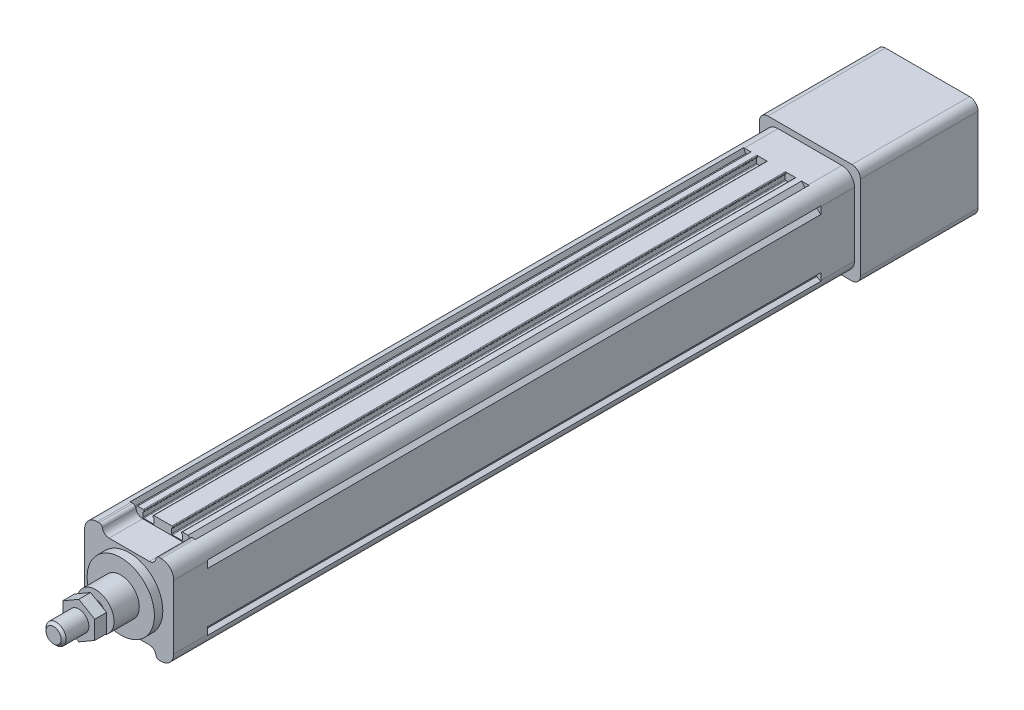
SolidWorks part; units mm, degrees
ref_plane "Front" through (0, 0, 0) normal (0, 0, 1) x (1, 0, 0)
ref_plane "Top" through (0, 0, 0) normal (0, 1, 0) x (1, 0, 0)
ref_plane "Right" through (0, 0, 0) normal (1, 0, 0) x (0, 0, -1)
sketch "草图1" plane through (0, 0, 0) normal (0, 0, 1) x (1, 0, 0)
  line L0 (19.7737, 3) -> (23.3, 3)
  line L1 (23.3, 3) -> (23.3, -3)
  line L2 (23.3, -3) -> (19.7737, -3)
  line L3 (-19.7737, -3) -> (-23.3, -3)
  line L4 (-23.3, -3) -> (-23.3, 3)
  line L5 (-23.3, 3) -> (-19.7737, 3)
  line L6 (-18.2, 24) -> (-19.4434, 26.4869)
  line L7 (-26.4869, 19.4434) -> (-24, 18.2)
  line L8 (-24, 18.2) -> (-24, 17.1)
  line L9 (-24, 17.1) -> (-26.5, 15)
  line L10 (-26.5, 15) -> (-26.5, -15)
  line L11 (-26.5, -15) -> (-24, -17.1)
  line L12 (-24, -17.1) -> (-24, -18.2)
  line L13 (-24, -18.2) -> (-26.4869, -19.4434)
  line L14 (-19.4434, -26.4869) -> (-18.2, -24)
  line L15 (-18.2, -24) -> (-17.1, -24)
  line L16 (-17.1, -24) -> (-15, -26.5)
  line L17 (-15, -26.5) -> (-11.65, -26.5)
  line L18 (-11.25, -26.1) -> (-11.25, -25.6)
  line L19 (-11.65, -25.2) -> (-11.75, -25.2)
  line L20 (-11.75, -25.2) -> (-11.75, -22.4)
  line L21 (-11.35, -22) -> (-5.65, -22)
  line L22 (-5.25, -22.4) -> (-5.25, -25.2)
  line L23 (-5.25, -25.2) -> (-5.35, -25.2)
  line L24 (-5.75, -25.6) -> (-5.75, -26.1)
  line L25 (-5.35, -26.5) -> (5.35, -26.5)
  line L26 (5.75, -26.1) -> (5.75, -25.6)
  line L27 (5.35, -25.2) -> (5.25, -25.2)
  line L28 (5.25, -25.2) -> (5.25, -22.4)
  line L29 (5.65, -22) -> (11.35, -22)
  line L30 (11.75, -22.4) -> (11.75, -25.2)
  line L31 (11.75, -25.2) -> (11.65, -25.2)
  line L32 (11.25, -25.6) -> (11.25, -26.1)
  line L33 (11.65, -26.5) -> (15, -26.5)
  line L34 (15, -26.5) -> (17.1, -24)
  line L35 (17.1, -24) -> (18.2, -24)
  line L36 (18.2, -24) -> (19.4434, -26.4869)
  line L37 (26.4869, -19.4434) -> (24, -18.2)
  line L38 (24, -18.2) -> (24, -17.1)
  line L39 (24, -17.1) -> (26.5, -15)
  line L40 (26.5, -15) -> (26.5, 15)
  line L41 (26.5, 15) -> (24, 17.1)
  line L42 (24, 17.1) -> (24, 18.2)
  line L43 (24, 18.2) -> (26.4869, 19.4434)
  line L44 (19.4434, 26.4869) -> (18.2, 24)
  line L45 (18.2, 24) -> (17.1, 24)
  line L46 (17.1, 24) -> (15, 26.5)
  line L47 (15, 26.5) -> (11.65, 26.5)
  line L48 (11.25, 26.1) -> (11.25, 25.6)
  line L49 (11.65, 25.2) -> (11.75, 25.2)
  line L50 (11.75, 25.2) -> (11.75, 22.4)
  line L51 (11.35, 22) -> (5.65, 22)
  line L52 (5.25, 22.4) -> (5.25, 25.2)
  line L53 (5.25, 25.2) -> (5.35, 25.2)
  line L54 (5.75, 25.6) -> (5.75, 26.1)
  line L55 (5.35, 26.5) -> (-5.35, 26.5)
  line L56 (-5.75, 26.1) -> (-5.75, 25.6)
  line L57 (-5.35, 25.2) -> (-5.25, 25.2)
  line L58 (-5.25, 25.2) -> (-5.25, 22.4)
  line L59 (-5.65, 22) -> (-11.35, 22)
  line L60 (-11.75, 22.4) -> (-11.75, 25.2)
  line L61 (-11.75, 25.2) -> (-11.65, 25.2)
  line L62 (-11.25, 25.6) -> (-11.25, 26.1)
  line L63 (-11.65, 26.5) -> (-15, 26.5)
  line L64 (-15, 26.5) -> (-17.1, 24)
  line L65 (-17.1, 24) -> (-18.2, 24)
  arc A0 (19.7737, 3) -> (-19.7737, 3) centre (0, 0) ccw
  arc A1 (-19.7737, -3) -> (19.7737, -3) centre (0, 0) ccw
  circle A2 centre (19, 19) radius 2.1
  circle A3 centre (19, -19) radius 2.1
  circle A4 centre (-19, -19) radius 2.1
  circle A5 centre (-19, 19) radius 2.1
  arc A6 (-19.4434, 26.4869) -> (-26.4869, 19.4434) centre (-19, 19) ccw
  arc A7 (-26.4869, -19.4434) -> (-19.4434, -26.4869) centre (-19, -19) ccw
  arc A8 (-11.65, -26.5) -> (-11.25, -26.1) centre (-11.65, -26.1) ccw
  arc A9 (-11.25, -25.6) -> (-11.65, -25.2) centre (-11.65, -25.6) ccw
  arc A10 (-11.35, -22) -> (-11.75, -22.4) centre (-11.35, -22.4) ccw
  arc A11 (-5.25, -22.4) -> (-5.65, -22) centre (-5.65, -22.4) ccw
  arc A12 (-5.35, -25.2) -> (-5.75, -25.6) centre (-5.35, -25.6) ccw
  arc A13 (-5.75, -26.1) -> (-5.35, -26.5) centre (-5.35, -26.1) ccw
  arc A14 (5.35, -26.5) -> (5.75, -26.1) centre (5.35, -26.1) ccw
  arc A15 (5.75, -25.6) -> (5.35, -25.2) centre (5.35, -25.6) ccw
  arc A16 (5.65, -22) -> (5.25, -22.4) centre (5.65, -22.4) ccw
  arc A17 (11.75, -22.4) -> (11.35, -22) centre (11.35, -22.4) ccw
  arc A18 (11.65, -25.2) -> (11.25, -25.6) centre (11.65, -25.6) ccw
  arc A19 (11.25, -26.1) -> (11.65, -26.5) centre (11.65, -26.1) ccw
  arc A20 (19.4434, -26.4869) -> (26.4869, -19.4434) centre (19, -19) ccw
  arc A21 (26.4869, 19.4434) -> (19.4434, 26.4869) centre (19, 19) ccw
  arc A22 (11.65, 26.5) -> (11.25, 26.1) centre (11.65, 26.1) ccw
  arc A23 (11.25, 25.6) -> (11.65, 25.2) centre (11.65, 25.6) ccw
  arc A24 (11.35, 22) -> (11.75, 22.4) centre (11.35, 22.4) ccw
  arc A25 (5.25, 22.4) -> (5.65, 22) centre (5.65, 22.4) ccw
  arc A26 (5.35, 25.2) -> (5.75, 25.6) centre (5.35, 25.6) ccw
  arc A27 (5.75, 26.1) -> (5.35, 26.5) centre (5.35, 26.1) ccw
  arc A28 (-5.35, 26.5) -> (-5.75, 26.1) centre (-5.35, 26.1) ccw
  arc A29 (-5.75, 25.6) -> (-5.35, 25.2) centre (-5.35, 25.6) ccw
  arc A30 (-5.65, 22) -> (-5.25, 22.4) centre (-5.65, 22.4) ccw
  arc A31 (-11.75, 22.4) -> (-11.35, 22) centre (-11.35, 22.4) ccw
  arc A32 (-11.65, 25.2) -> (-11.25, 25.6) centre (-11.65, 25.6) ccw
  arc A33 (-11.25, 26.1) -> (-11.65, 26.5) centre (-11.65, 26.1) ccw
extrude "凸台-拉伸1" add sketch "草图1" along normal blind 365
sketch "草图6" plane through (0, 0, 365) normal (0, 0, 1) x (1, 0, 0)
  line L0 (0, 0) -> (19, 0) construction
  line L2 (-26.5, -19) -> (-26.5, 19)
  line L3 (-19, 26.5) -> (-17.9161, 26.5)
  line L4 (26.5, -19) -> (26.5, 19)
  line L5 (-26.5, -26.5) -> (26.5, 26.5) construction
  line L6 (-26.5, 26.5) -> (26.5, -26.5) construction
  line L7 (-12, 21.5) -> (12, 21.5)
  line L9 (19, 26.5) -> (17.9161, 26.5)
  line L10 (19, -26.5) -> (17.9161, -26.5)
  line L11 (-12, -21.5) -> (12, -21.5)
  line L12 (-19, -26.5) -> (-17.9161, -26.5)
  arc A0 (12, 21.5) -> (15.9441, 24.8333) centre (12, 25.5) ccw
  arc A1 (-15.9441, 24.8333) -> (-12, 21.5) centre (-12, 25.5) ccw
  arc A2 (-15.9441, 24.8333) -> (-17.9161, 26.5) centre (-17.9161, 24.5) ccw
  arc A3 (15.9441, 24.8333) -> (17.9161, 26.5) centre (17.9161, 24.5) cw
  arc A4 (-26.5, -19) -> (-19, -26.5) centre (-19, -19) ccw
  arc A5 (19, -26.5) -> (26.5, -19) centre (19, -19) ccw
  arc A6 (26.5, 19) -> (19, 26.5) centre (19, 19) ccw
  arc A7 (-26.5, 19) -> (-19, 26.5) centre (-19, 19) cw
  arc A8 (15.9441, -24.8333) -> (17.9161, -26.5) centre (17.9161, -24.5) ccw
  arc A9 (12, -21.5) -> (15.9441, -24.8333) centre (12, -25.5) cw
  arc A10 (-15.9441, -24.8333) -> (-12, -21.5) centre (-12, -25.5) cw
  arc A11 (-15.9441, -24.8333) -> (-17.9161, -26.5) centre (-17.9161, -24.5) cw
  point P0 (0, 0)
  point P9 (0, 21.5)
  point P13 (20, 20.8461)
  point P16 (-12, 20.8461)
  dimension "D5" = 4
  dimension "D6" = 2
  dimension "D7" = 2
  dimension "D9" = 7.5
  dimension "D1" = 53
  dimension "D2" = 53
  dimension "D3" = 26.5
  dimension "D4" = 24
  dimension "D8" = 5
extrude "凸台-拉伸2" add sketch "草图6" along normal blind 20
sketch "草图7" plane through (0, 0, 385) normal (0, 0, 1) x (1, 0, 0)
  circle A0 centre (0, 0) radius 20
  dimension "D1" = 40
extrude "凸台-拉伸3" add sketch "草图7" along normal blind 5
sketch "草图9" plane through (0, 0, 390) normal (0, 0, 1) x (1, 0, 0)
  circle A0 centre (0, 0) radius 11
  dimension "D1" = 22
extrude "凸台-拉伸4" add sketch "草图9" along normal blind 15
sketch "草图10" plane through (0, 0, 405) normal (0, 0, 1) x (1, 0, 0)
  circle A0 centre (0, 0) radius 6
  dimension "D1" = 12
extrude "凸台-拉伸5" add sketch "草图10" along normal blind 25
sketch "草图11" plane through (0, 0, 0) normal (0, 0, -1) x (-1, 0, 0)
  line L1 (-19, -26.5) -> (19, -26.5)
  line L2 (-26.5, -19) -> (-26.5, 19)
  line L3 (-19, 26.5) -> (19, 26.5)
  line L4 (26.5, -19) -> (26.5, 19)
  line L5 (-26.5, -26.5) -> (26.5, 26.5) construction
  line L6 (-26.5, 26.5) -> (26.5, -26.5) construction
  arc A0 (-26.5, -19) -> (-19, -26.5) centre (-19, -19) ccw
  arc A1 (19, -26.5) -> (26.5, -19) centre (19, -19) ccw
  arc A2 (26.5, 19) -> (19, 26.5) centre (19, 19) ccw
  arc A3 (-26.5, 19) -> (-19, 26.5) centre (-19, 19) cw
  point P0 (0, 0)
  dimension "D3" = 7.5
  dimension "D1" = 53
  dimension "D2" = 53
extrude "凸台-拉伸6" add sketch "草图11" along normal blind 20
sketch "草图12" plane through (0, 0, -20) normal (0, 0, -1) x (-1, 0, 0)
  line L1 (-25, -30) -> (25, -30)
  line L2 (-30, -25) -> (-30, 25)
  line L3 (-25, 30) -> (25, 30)
  line L4 (30, -25) -> (30, 25)
  line L5 (-30, -30) -> (30, 30) construction
  line L6 (-30, 30) -> (30, -30) construction
  arc A0 (-30, -25) -> (-25, -30) centre (-25, -25) ccw
  arc A1 (25, -30) -> (30, -25) centre (25, -25) ccw
  arc A2 (30, 25) -> (25, 30) centre (25, 25) ccw
  arc A3 (-30, 25) -> (-25, 30) centre (-25, 25) cw
  point P0 (0, 0)
  dimension "D3" = 5
  dimension "D1" = 60
  dimension "D2" = 60
extrude "凸台-拉伸7" add sketch "草图12" along normal blind 70
sketch "草图14" plane through (0, 0, -90) normal (0, 0, -1) x (-1, 0, 0)
  circle A0 centre (0, 0) radius 19
  dimension "D1" = 38
extrude "切除-拉伸2" cut sketch "草图14" against normal blind 70
hole_wizard "M6 螺纹孔1" positions "草图15" profile "草图16" tap size "M6" standard "GB"
sketch "草图15" plane through (-26.5, 0, 0) normal (-1, 0, 0) x (0, 0, 1)
  line L0 (-20, -25) -> (-20, 25) construction
  line L1 (385, 19) -> (385, -19) construction
  point P0 (375, 11)
  point P2 (375, -11)
  point P4 (-10, 11)
  point P6 (-10, -11)
  dimension "D1" = 10
  dimension "D2" = 10
  dimension "D3" = 11
  dimension "D4" = 11
  dimension "D5" = 10
  dimension "D6" = 10
  dimension "D7" = 22
  dimension "D8" = 11
sketch "草图16" plane through (-26.5, 11, 375) normal (0, 1, 0) x (0, 0, 1)
  line L0 (0, 0) -> (0, 16.5022)
  line L1 (0, 16.5022) -> (2.5, 15)
  line L2 (2.5, 15) -> (2.5, 0)
  line L5 (2.5, 0) -> (0, 0)
  line L10 (0, 16.5022) -> (-2.5, 15) construction
  line L11 (0, -6.35) -> (0, 107.95) construction
  dimension "螺纹孔钻头直径" = 5
  dimension "螺纹孔钻头深度" = 15
  dimension "导头角度" = 118
cosmetic thread "孔螺蚊线4" parameters "D1"=12, "D2"=6
cosmetic thread "孔螺蚊线5" parameters "D1"=12, "D2"=6
cosmetic thread "孔螺蚊线6" parameters "D1"=12, "D2"=6
cosmetic thread "孔螺蚊线7" parameters "D1"=12, "D2"=6
chamfer "倒角1" distance 1.5 angle 45 1 edges at (6, 0, 430)
sketch "草图17" plane through (0, 0, 405) normal (0, 0, 1) x (1, 0, 0)
  line L1 (0, 10.9697) -> (-9.5, 5.4848)
  line L2 (-9.5, 5.4848) -> (-9.5, -5.4848)
  line L3 (-9.5, -5.4848) -> (0, -10.9697)
  line L4 (0, -10.9697) -> (9.5, -5.4848)
  line L5 (9.5, -5.4848) -> (9.5, 5.4848)
  line L6 (9.5, 5.4848) -> (0, 10.9697)
  circle A0 centre (0, 0) radius 9.5 construction
  dimension "D1" = 19
extrude "凸台-拉伸8" add sketch "草图17" along normal blind 7 from offset 3
